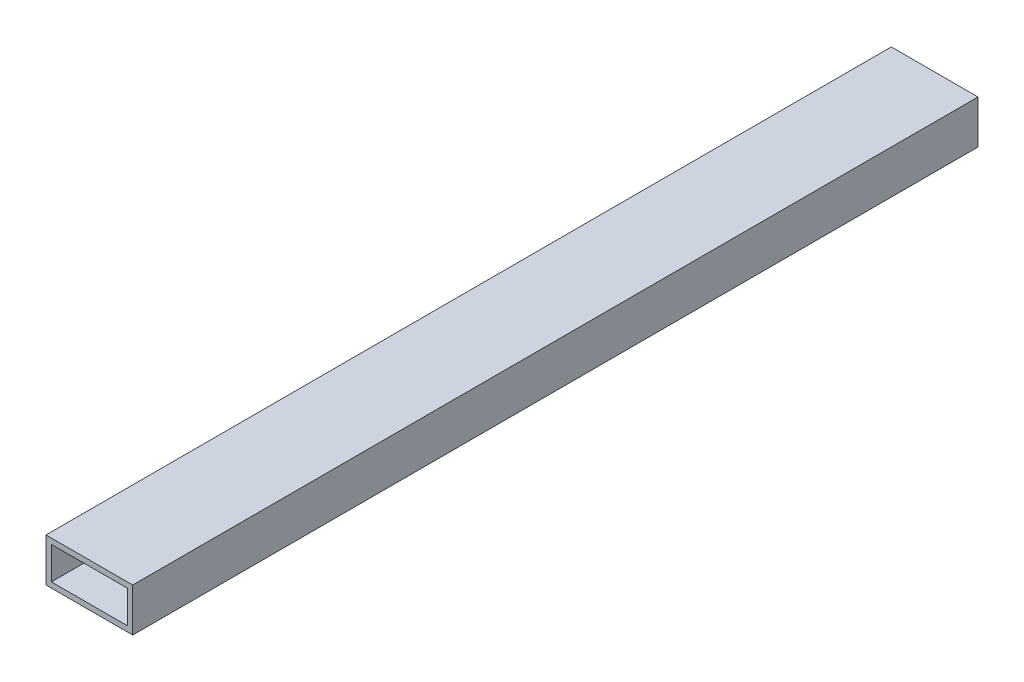
SolidWorks part; units mm, degrees
ref_plane "Front Plane" through (0, 0, 0) normal (0, 0, 1) x (1, 0, 0)
ref_plane "Top Plane" through (0, 0, 0) normal (0, 1, 0) x (1, 0, 0)
ref_plane "Right Plane" through (0, 0, 0) normal (1, 0, 0) x (0, 0, -1)
sketch "Sketch1" plane through (0, 0, 0) normal (0, 0, 1) x (1, 0, 0)
  line L0 (3.175, 22.225) -> (47.625, 22.225)
  line L1 (0, 0) -> (50.8, 0)
  line L2 (0, 0) -> (0, 25.4)
  line L3 (0, 25.4) -> (50.8, 25.4)
  line L4 (50.8, 0) -> (50.8, 25.4)
  line L5 (47.625, 3.175) -> (47.625, 22.225)
  line L6 (3.175, 3.175) -> (47.625, 3.175)
  line L7 (3.175, 3.175) -> (3.175, 22.225)
  dimension "D1" = 50.8
  dimension "D2" = 25.4
  dimension "D3" = 3.175
extrude "Boss-Extrude1" add sketch "Sketch1" along normal blind 495.3
